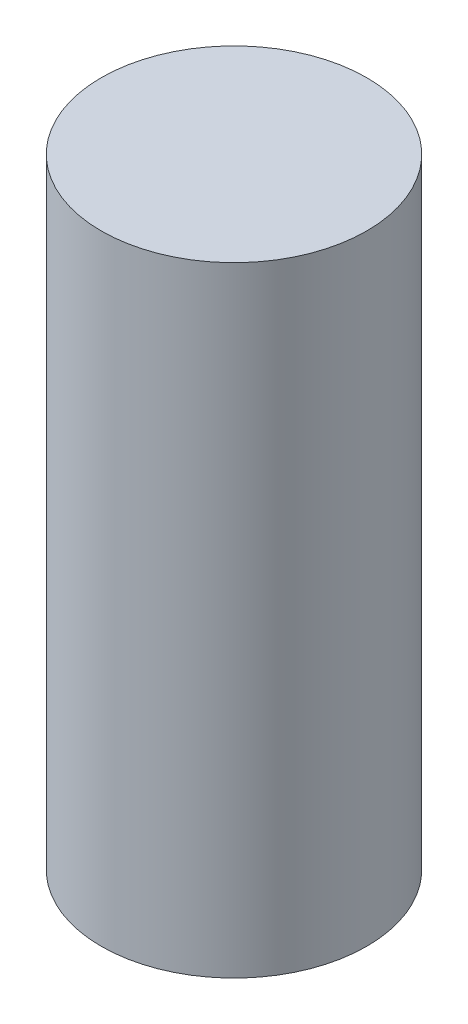
SolidWorks part; units mm, degrees
ref_plane "Front Plane" through (0, 0, 0) normal (0, 0, 1) x (1, 0, 0)
ref_plane "Top Plane" through (0, 0, 0) normal (0, 1, 0) x (1, 0, 0)
ref_plane "Right Plane" through (0, 0, 0) normal (1, 0, 0) x (0, 0, -1)
other "Configuration Table"
sketch "Sketch1" plane through (0, 0, 0) normal (0, 1, 0) x (1, 0, 0)
  circle A0 centre (50, 50) radius 6
extrude "PACK_ayar_mil_1" add sketch "Sketch1" along normal blind 28 from offset 12 separate body
